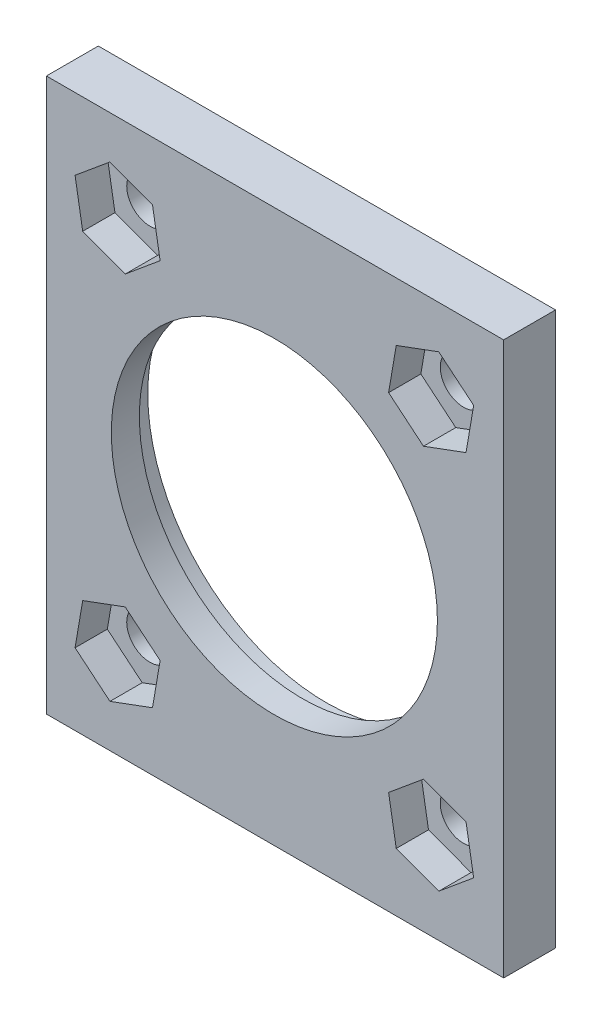
SolidWorks part; units mm, degrees
ref_plane "Front Plane" through (0, 0, 0) normal (0, 0, 1) x (1, 0, 0)
ref_plane "Top Plane" through (0, 0, 0) normal (0, 1, 0) x (1, 0, 0)
ref_plane "Right Plane" through (0, 0, 0) normal (1, 0, 0) x (0, 0, -1)
sketch "Sketch2" plane through (0, 0, 0) normal (0, 0, 1) x (1, 0, 0)
  line L0 (-16.4525, 19.898) -> (16.5456, 19.902) construction
  line L1 (16.5506, -20.098) -> (16.5459, 17.9015) construction
  line L2 (-16.4475, -20.102) -> (-16.4522, 17.9012) construction
  line L3 (-16.4525, 19.898) -> (16.5456, 19.902) construction
  line L4 (16.5506, -20.098) -> (16.5459, 17.9015) construction
  line L5 (-16.4475, -20.102) -> (-16.4522, 17.9012) construction
  line L6 (-16.2476, -19.702) -> (-16.2524, 19.698)
  line L7 (16.3505, -19.698) -> (16.3457, 19.702)
  line L8 (-16.2524, 19.698) -> (16.3457, 19.702)
  line L9 (16.3506, -20.098) -> (16.3459, 17.9015) construction
  line L10 (-16.4524, 19.698) -> (16.5457, 19.702) construction
  line L11 (-16.2475, -20.102) -> (-16.2522, 17.9012) construction
  line L12 (-16.2476, -19.702) -> (16.3505, -19.698)
  line L13 (0, 0) -> (0.0466, 19.7) construction
  line L14 (0, 0) -> (0.0515, -19.7) construction
  circle A0 centre (0, 0) radius 11.425 construction
  circle A1 centre (0, 0) radius 11.425 construction
  circle A2 centre (0, 0) radius 11.625
  dimension "D5" = 39.4
  dimension "D6" = 32.5981
  dimension "D1" = 0.2
  dimension "D2" = 0.2
  dimension "D3" = 0.2
  dimension "D4" = 0.2
extrude "Boss-Extrude1" add sketch "Sketch2" against normal up to surface (2 mm away)
sketch "Sketch3" plane through (0, 0, -2) normal (0, 0, -1) x (-1, 0, 0)
  line L4 (-16.3505, -19.698) -> (16.2476, -19.702)
  line L5 (16.2476, -19.702) -> (16.2524, 19.698)
  line L6 (16.2524, 19.698) -> (-16.3457, 19.702)
  line L7 (-16.3457, 19.702) -> (-16.3505, -19.698)
  line L8 (-16.3505, -19.698) -> (16.2476, -19.702)
  line L9 (16.2476, -19.702) -> (16.2524, 19.698)
  line L10 (16.2524, 19.698) -> (-16.3457, 19.702)
  line L11 (-16.3457, 19.702) -> (-16.3505, -19.698)
  circle A0 centre (0, 0) radius 12.425 construction
  circle A1 centre (0, 0) radius 12.425 construction
  circle A2 centre (0, 0) radius 12.725
  dimension "D1" = 0.3
  dimension "D2" = 0
extrude "Boss-Extrude2" add sketch "Sketch3" along normal offset from surface (1.7 mm away) 0.3
sketch "Sketch4" plane through (0, 0, 0) normal (0, 0, 1) x (1, 0, 0)
  line L0 (0, 0) -> (16.3505, -19.698) construction
  line L1 (13.665, -11.4005) -> (8.6894, -15.5305) construction
  line L2 (10.6327, -10.2785) -> (8.145, -12.3435)
  line L3 (8.145, -12.3435) -> (8.6894, -15.5305)
  line L4 (8.6894, -15.5305) -> (11.7217, -16.6525)
  line L5 (11.7217, -16.6525) -> (14.2094, -14.5875)
  line L6 (14.2094, -14.5875) -> (13.665, -11.4005)
  line L7 (13.665, -11.4005) -> (10.6327, -10.2785)
  line L8 (0, 0) -> (1.9413, 0) construction
  line L9 (0, 0) -> (0, 2.2527) construction
  line L10 (13.665, 11.4005) -> (10.6327, 10.2785)
  line L11 (14.2094, 14.5875) -> (13.665, 11.4005)
  line L12 (11.7217, 16.6525) -> (14.2094, 14.5875)
  line L13 (8.6894, 15.5305) -> (11.7217, 16.6525)
  line L14 (8.145, 12.3435) -> (8.6894, 15.5305)
  line L15 (10.6327, 10.2785) -> (8.145, 12.3435)
  line L16 (-13.665, 11.4005) -> (-10.6327, 10.2785)
  line L17 (-10.6327, 10.2785) -> (-8.145, 12.3435)
  line L18 (-8.145, 12.3435) -> (-8.6894, 15.5305)
  line L19 (-8.6894, 15.5305) -> (-11.7217, 16.6525)
  line L20 (-11.7217, 16.6525) -> (-14.2094, 14.5875)
  line L21 (-14.2094, 14.5875) -> (-13.665, 11.4005)
  line L22 (-13.665, -11.4005) -> (-10.6327, -10.2785)
  line L23 (-14.2094, -14.5875) -> (-13.665, -11.4005)
  line L24 (-11.7217, -16.6525) -> (-14.2094, -14.5875)
  line L25 (-8.6894, -15.5305) -> (-11.7217, -16.6525)
  line L26 (-8.145, -12.3435) -> (-8.6894, -15.5305)
  line L27 (-10.6327, -10.2785) -> (-8.145, -12.3435)
  circle A0 centre (0, 0) radius 11.625 construction
  circle A1 centre (0, 0) radius 11.625 construction
  circle A2 centre (0, 0) radius 17.5 construction
  circle A3 centre (11.1772, -13.4655) radius 2.8 construction
  point P0 (12.9252, -11.5145)
  dimension "D2" = 35
  dimension "D1" = 5.6
extrude "Cut-Extrude1" cut sketch "Sketch4" against normal blind 2.3
sketch "Sketch5" plane through (0, 0, -3.7) normal (0, 0, -1) x (-1, 0, 0)
  line L0 (0, 0) -> (0, -0.9964) construction
  line L1 (0, 0) -> (-1.316, 0) construction
  circle A0 centre (0, 0) radius 17.5 construction
  circle A1 centre (0, 0) radius 17.5 construction
  circle A2 centre (-11.1772, -13.4655) radius 2.8 construction
  circle A3 centre (-11.1772, -13.4655) radius 2.8 construction
  circle A4 centre (-11.1772, -13.4655) radius 1.65
  circle A5 centre (-11.1772, 13.4655) radius 1.65
  circle A6 centre (11.1772, 13.4655) radius 1.65
  circle A7 centre (11.1772, -13.4655) radius 1.65
  dimension "D1" = 3.3
extrude "Cut-Extrude2" cut sketch "Sketch5" against normal up to surface (1.4 mm away) up to face at (11.1772, -13.4655, -2.3)
